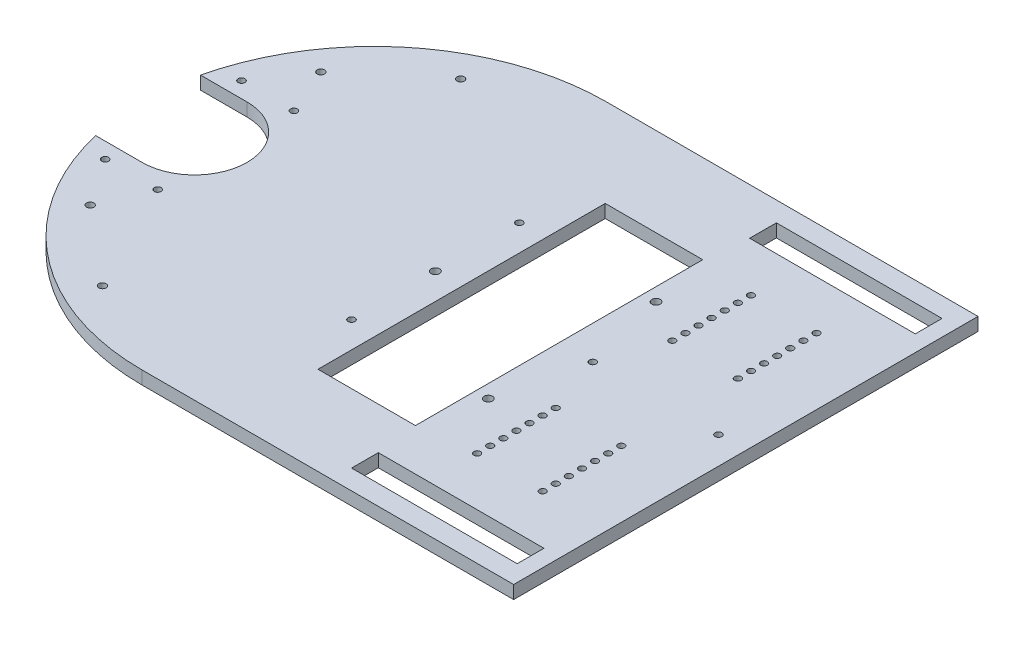
SolidWorks part; units mm, degrees
ref_plane "Front Plane" through (0, 0, 0) normal (0, 0, 1) x (1, 0, 0)
ref_plane "Top Plane" through (0, 0, 0) normal (0, 1, 0) x (1, 0, 0)
ref_plane "Right Plane" through (0, 0, 0) normal (1, 0, 0) x (0, 0, -1)
sketch "Sketch1" plane through (0, 0, 0) normal (0, 1, 0) x (1, 0, 0)
  line L0 (0, -112.5) -> (0, 0) construction
  line L1 (-80, 112.5) -> (100, 112.5)
  line L3 (-80, -112.5) -> (100, -112.5)
  line L4 (100, 112.5) -> (100, -112.5)
  line L5 (0, 0) -> (0, 112.5) construction
  arc A0 (-80, 112.5) -> (-80, -112.5) centre (-80, 0) ccw
  dimension "D1" = 100
  dimension "D4" = 112.5
  dimension "D2" = 80
  dimension "D3" = 225
extrude "Boss-Extrude1" add sketch "Sketch1" against normal blind 6.35
sketch "Sketch2" plane through (0, 0, 0) normal (0, 1, 0) x (1, 0, 0)
  line L0 (36.144, -66.3448) -> (36.144, -59.9948) construction
  line L1 (52.019, 0) -> (52.019, -89.9668) construction
  line L2 (11.887, -89.9668) -> (92.151, -89.9668)
  line L3 (11.887, -89.9668) -> (11.887, -102.9208)
  line L4 (11.887, -102.9208) -> (92.151, -102.9208)
  line L5 (92.151, -89.9668) -> (92.151, -102.9208)
  line L6 (11.887, 89.9668) -> (92.151, 89.9668)
  line L7 (11.887, 89.9668) -> (11.887, 102.9208)
  line L8 (11.887, 102.9208) -> (92.151, 102.9208)
  line L9 (92.151, 89.9668) -> (92.151, 102.9208)
  line L10 (52.019, 0) -> (52.019, 89.9668) construction
  line L11 (36.144, -59.9948) -> (36.144, -53.6448) construction
  line L12 (36.144, -53.6448) -> (36.144, -47.2948) construction
  line L13 (36.144, -47.2948) -> (36.144, -40.9448) construction
  line L14 (36.144, -40.9448) -> (36.144, -34.5948) construction
  line L15 (36.144, -34.5948) -> (36.144, -28.2448) construction
  line L16 (67.894, -66.3448) -> (67.894, -59.9948) construction
  line L17 (67.894, -59.9948) -> (67.894, -53.6448) construction
  line L18 (67.894, -53.6448) -> (67.894, -47.2948) construction
  line L19 (67.894, -47.2948) -> (67.894, -40.9448) construction
  line L20 (67.894, -40.9448) -> (67.894, -34.5948) construction
  line L21 (67.894, -34.5948) -> (67.894, -28.2448) construction
  line L22 (36.144, -66.3448) -> (67.894, -66.3448) construction
  line L23 (36.144, -28.2448) -> (67.894, -28.2448) construction
  line L24 (36.144, 28.2448) -> (36.144, 34.5948) construction
  line L25 (36.144, 34.5948) -> (36.144, 40.9448) construction
  line L26 (36.144, 40.9448) -> (36.144, 47.2948) construction
  line L27 (36.144, 47.2948) -> (36.144, 53.6448) construction
  line L28 (36.144, 53.6448) -> (36.144, 59.9948) construction
  line L29 (36.144, 59.9948) -> (36.144, 66.3448) construction
  line L30 (67.894, 28.2448) -> (67.894, 34.5948) construction
  line L31 (67.894, 34.5948) -> (67.894, 40.9448) construction
  line L32 (67.894, 40.9448) -> (67.894, 47.2948) construction
  line L33 (67.894, 47.2948) -> (67.894, 53.6448) construction
  line L34 (67.894, 53.6448) -> (67.894, 59.9948) construction
  line L35 (67.894, 59.9948) -> (67.894, 66.3448) construction
  line L36 (36.144, 66.3448) -> (67.894, 66.3448) construction
  line L37 (36.144, 28.2448) -> (67.894, 28.2448) construction
  line L38 (36.144, 47.2948) -> (52.019, 47.2948) construction
  line L39 (52.019, 47.2948) -> (67.894, 47.2948) construction
  line L40 (0, -112.5) -> (0, 112.5) construction
  line L41 (0, 0) -> (52.019, 0) construction
  line L42 (100, 112.5) -> (-80, 112.5) construction
  line L43 (-80, -112.5) -> (100, -112.5) construction
  circle A1 centre (36.144, -66.3448) radius 1.5875
  circle A2 centre (36.144, -59.9948) radius 1.5875
  circle A3 centre (36.144, -53.6448) radius 1.5875
  circle A4 centre (36.144, -47.2948) radius 1.5875
  circle A5 centre (36.144, -40.9448) radius 1.5875
  circle A6 centre (36.144, -34.5948) radius 1.5875
  circle A7 centre (36.144, -28.2448) radius 1.5875
  circle A8 centre (67.894, -66.3448) radius 1.5875
  circle A9 centre (67.894, -59.9948) radius 1.5875
  circle A10 centre (67.894, -53.6448) radius 1.5875
  circle A11 centre (67.894, -47.2948) radius 1.5875
  circle A12 centre (67.894, -40.9448) radius 1.5875
  circle A13 centre (67.894, -34.5948) radius 1.5875
  circle A14 centre (67.894, -28.2448) radius 1.5875
  circle A15 centre (36.144, 66.3448) radius 1.5875
  circle A16 centre (36.144, 59.9948) radius 1.5875
  circle A17 centre (36.144, 53.6448) radius 1.5875
  circle A18 centre (36.144, 47.2948) radius 1.5875
  circle A19 centre (36.144, 40.9448) radius 1.5875
  circle A20 centre (36.144, 34.5948) radius 1.5875
  circle A21 centre (36.144, 28.2448) radius 1.5875
  circle A22 centre (67.894, 66.3448) radius 1.5875
  circle A23 centre (67.894, 59.9948) radius 1.5875
  circle A24 centre (67.894, 53.6448) radius 1.5875
  circle A25 centre (67.894, 47.2948) radius 1.5875
  circle A26 centre (67.894, 40.9448) radius 1.5875
  circle A27 centre (67.894, 34.5948) radius 1.5875
  circle A28 centre (67.894, 28.2448) radius 1.5875
  dimension "D6" = 3.175
  dimension "D7" = 6.35
  dimension "D8" = 15.875
  dimension "D10" = 3.175
  dimension "D1" = 12.954
  dimension "D2" = 80.264
  dimension "D3" = 179.9336
  dimension "D4" = 23.622
  dimension "D5" = 15.875
  dimension "D9" = 15.875
  dimension "D11" = 6.35
  dimension "D12" = 23.622
  dimension "D13" = 56.4896
  dimension "D14" = 205.8416
  dimension "D15" = 92.151
extrude "Cut-Extrude1" cut sketch "Sketch2" against normal through all
sketch "Sketch7" plane through (0, 0, 0) normal (0, 1, 0) x (1, 0, 0)
  line L0 (10, 112.5) -> (9.5225, 69.596) construction
  line L1 (-37.7215, 69.596) -> (9.5225, 69.596)
  line L2 (-37.7215, 69.596) -> (-37.7215, -69.596)
  line L3 (-37.7215, -69.596) -> (9.5225, -69.596)
  line L4 (9.5225, 69.596) -> (9.5225, -69.596)
  line L5 (100, 112.5) -> (-80, 112.5) construction
  line L6 (9.5225, -69.596) -> (10, -112.5) construction
  line L7 (-80, -112.5) -> (100, -112.5) construction
  line L8 (-50.4215, -40.64) -> (-50.4215, 0) construction
  line L9 (-50.4215, 0) -> (-50.4215, 40.64) construction
  circle A0 centre (-50.4215, 0) radius 2.032
  circle A1 centre (25.7785, 0) radius 1.651
  circle A2 centre (86.7385, 0) radius 1.651
  circle A3 centre (-50.4215, 40.64) radius 1.651
  circle A4 centre (-50.4215, -40.64) radius 1.651
  circle A5 centre (15.8725, -40.64) radius 2.032
  circle A6 centre (15.8725, 40.64) radius 2.032
  dimension "D3" = 4.064
  dimension "D5" = 40.64
  dimension "D9" = 3.302
  dimension "D10" = 3.302
  dimension "D11" = 3.302
  dimension "D12" = 4.064
  dimension "D13" = 4.064
  dimension "D1" = 47.244
  dimension "D2" = 139.192
  dimension "D4" = 12.7
  dimension "D6" = 6.35
  dimension "D7" = 16.256
  dimension "D8" = 60.96
extrude "Cut-Extrude4" cut sketch "Sketch7" against normal through all
sketch "Sketch8" plane through (0, 0, 0) normal (0, 1, 0) x (1, 0, 0)
  line L0 (-80, 112.5) -> (-80, -112.5) construction
  line L1 (-192.5, 0) -> (100, 0) construction
  line L2 (100, -112.5) -> (100, 112.5) construction
  line L3 (-167.0966, 25.4) -> (-229.7767, 25.4)
  line L4 (-229.7767, 25.4) -> (-229.7767, -25.4)
  line L5 (-229.7767, -25.4) -> (-167.0966, -25.4)
  line L6 (-182.2096, 12.065) -> (-182.2096, -12.065) construction
  line L7 (-182.2096, -12.065) -> (-151.9836, -12.065) construction
  line L8 (-151.9836, -12.065) -> (-151.9836, 12.065) construction
  line L9 (-151.9836, 12.065) -> (-182.2096, 12.065) construction
  arc A0 (-80, 112.5) -> (-80, -112.5) centre (-80, 0) ccw construction
  circle A1 centre (-177.3836, 33.02) radius 1.651
  arc A2 (-167.0966, 25.4) -> (-167.0966, -25.4) centre (-167.0966, 0) cw
  circle A3 centre (-177.3836, -33.02) radius 1.651
  circle A4 centre (-151.9836, 33.02) radius 1.651
  circle A5 centre (-151.9836, -33.02) radius 1.651
  point P12 (-80, 0)
  point P19 (-151.9836, 0)
  point P22 (-167.0966, 12.065)
  dimension "D2" = 87.0966
  dimension "D1" = 25.4
  dimension "D6" = 33.02
  dimension "D11" = 3.302
  dimension "D3" = 112.5
  dimension "D4" = 30.226
  dimension "D5" = 24.13
  dimension "D7" = 33.02
  dimension "D8" = 33.02
  dimension "D9" = 33.02
  dimension "D10" = 25.4
extrude "Cut-Extrude5" cut sketch "Sketch8" against normal through all
sketch "Sketch9" plane through (0, 0, 0) normal (0, 1, 0) x (1, 0, 0)
  line L0 (-161.7953, 55.88) -> (-124.9646, 86.7846) construction
  line L1 (-161.7953, -55.88) -> (-124.9646, -86.7846) construction
  line L2 (-161.7953, -55.88) -> (-125.8605, -55.88) construction
  line L3 (-161.7953, 55.88) -> (-125.8605, 55.88) construction
  circle A0 centre (-161.7953, -55.88) radius 1.778
  circle A1 centre (-124.9646, -86.7846) radius 1.778
  circle A2 centre (-161.7953, 55.88) radius 1.778
  circle A3 centre (-124.9646, 86.7846) radius 1.778
  arc A4 (-167.0966, -25.4) -> (-167.0966, 25.4) centre (-167.0966, 0) ccw construction
  point P8 (-141.6966, 0)
  point P14 (-141.6966, 0)
  point P16 (-138.8589, -1.9001)
  dimension "D5" = 3.556
  dimension "D1" = 40
  dimension "D2" = 40
  dimension "D3" = 55.88
  dimension "D4" = 55.88
extrude "Cut-Extrude6" cut sketch "Sketch9" against normal through all
